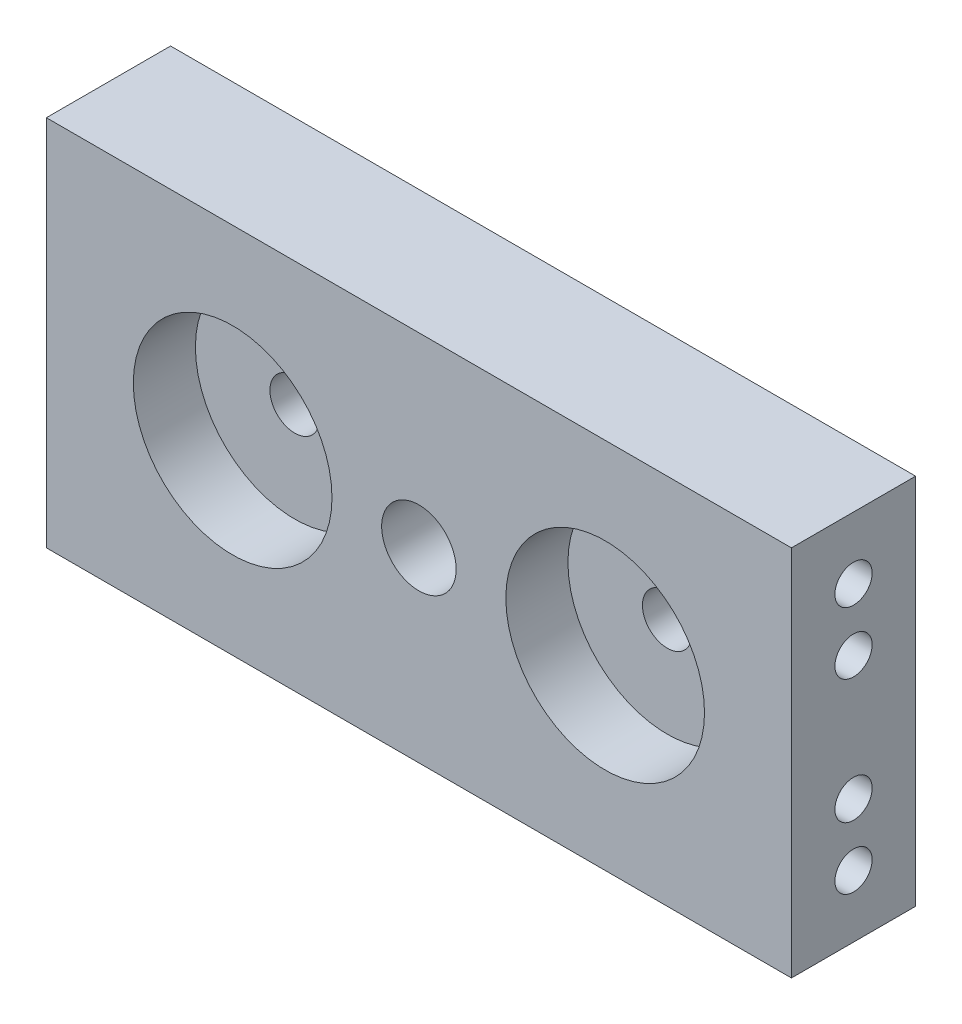
SolidWorks part; units mm, degrees
ref_plane "Front Plane" through (0, 0, 0) normal (0, 0, 1) x (1, 0, 0)
ref_plane "Top Plane" through (0, 0, 0) normal (0, 1, 0) x (1, 0, 0)
ref_plane "Right Plane" through (0, 0, 0) normal (1, 0, 0) x (0, 0, -1)
sketch "Sketch1" plane through (0, 0, 0) normal (0, 0, 1) x (1, 0, 0)
  line L0 (0, 0) -> (120, 0)
  line L1 (120, 0) -> (120, -60)
  line L2 (120, -60) -> (0, -60)
  line L3 (0, -60) -> (0, 0)
  line L4 (60, 0) -> (60, -60)
  line L5 (60, -30) -> (90, -30)
  line L6 (60, -30) -> (30, -30)
extrude "Boss-Extrude1" add sketch "Sketch1" along normal blind 20
sketch "Sketch2" plane through (0, 0, 20) normal (0, 0, 1) x (1, 0, 0)
  line L0 (60, 0) -> (60, -60)
  line L1 (0, 0) -> (120, 0) construction
  line L2 (120, -60) -> (0, -60) construction
  line L3 (60, -30) -> (90, -30)
  line L4 (60, -30) -> (30, -30)
  circle A0 centre (30, -30) radius 4
  circle A1 centre (60, -30) radius 6
  circle A2 centre (90, -30) radius 4
extrude "Cut-Extrude1" cut sketch "Sketch2" against normal blind 20
sketch "Sketch3" plane through (0, 0, 20) normal (0, 0, 1) x (1, 0, 0)
  circle A0 centre (30, -30) radius 16
  circle A1 centre (90, -30) radius 16
  circle M3 centre (90, -30) radius 4
  circle M4 centre (30, -30) radius 4
extrude "Cut-Extrude2" cut sketch "Sketch3" against normal blind 10 contours A0 M4 | A1 M3
sketch "Sketch4" plane through (120, 0, 0) normal (1, 0, 0) x (0, 0, -1)
  line L0 (-10, 0) -> (-10, -20)
  line L1 (-20, 0) -> (0, 0) construction
  line L2 (-10, -20) -> (-10, -10)
  line L3 (-10, -60) -> (-10, -40)
  line L4 (-20, -60) -> (0, -60) construction
  line L5 (-10, -40) -> (-10, -50)
  circle A0 centre (-10, -10) radius 3
  circle A1 centre (-10, -20) radius 3
  circle A2 centre (-10, -40) radius 3
  circle A3 centre (-10, -50) radius 3
extrude "Cut-Extrude4" cut sketch "Sketch4" against normal blind 10 contours A0 | A1 | A2 | A3
sketch "Sketch5" plane through (0, 0, 0) normal (-1, 0, 0) x (0, 0, 1)
  line L0 (10, 0) -> (10, -20)
  line L1 (20, 0) -> (0, 0) construction
  line L2 (10, -20) -> (10, -10)
  line L3 (10, -60) -> (10, -40)
  line L4 (20, -60) -> (0, -60) construction
  line L5 (10, -40) -> (10, -50)
  circle A0 centre (10, -10) radius 3
  circle A1 centre (10, -20) radius 3
  circle A2 centre (10, -40) radius 3
  circle A3 centre (10, -50) radius 3
extrude "Cut-Extrude5" cut sketch "Sketch5" against normal blind 10 contours A0 | A1 | A2 | A3
